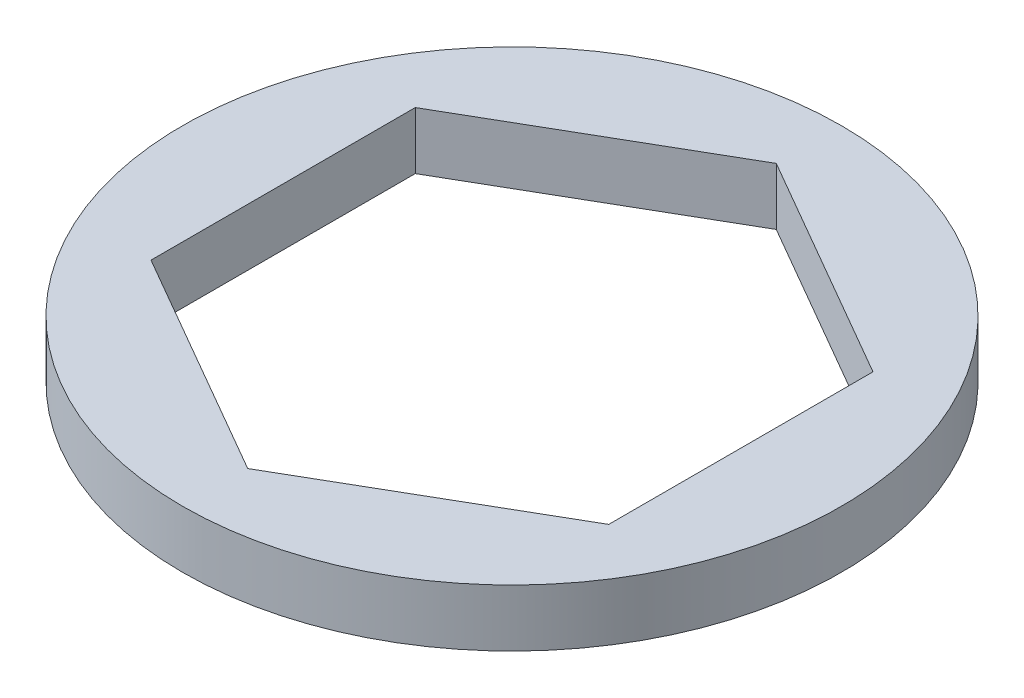
SolidWorks part; units mm, degrees
ref_plane "Front Plane" through (0, 0, 0) normal (0, 0, 1) x (1, 0, 0)
ref_plane "Top Plane" through (0, 0, 0) normal (0, 1, 0) x (1, 0, 0)
ref_plane "Right Plane" through (0, 0, 0) normal (1, 0, 0) x (0, 0, -1)
sketch "Sketch1" plane through (0, 0, 0) normal (0, 1, 0) x (1, 0, 0)
  line L0 (0, 0) -> (0, 7.3323) construction
  line L1 (6.35, -3.6662) -> (6.35, 3.6662)
  line L2 (6.35, 3.6662) -> (0, 7.3323)
  line L3 (0, 7.3323) -> (-6.35, 3.6662)
  line L4 (-6.35, 3.6662) -> (-6.35, -3.6662)
  line L5 (-6.35, -3.6662) -> (0, -7.3323)
  line L6 (0, -7.3323) -> (6.35, -3.6662)
  circle A0 centre (0, 0) radius 6.35 construction
  circle A1 centre (0, 0) radius 9.144
  dimension "D1" = 12.7
  dimension "D2" = 18.288
extrude "Boss-Extrude1" add sketch "Sketch1" along normal blind 1.5875
